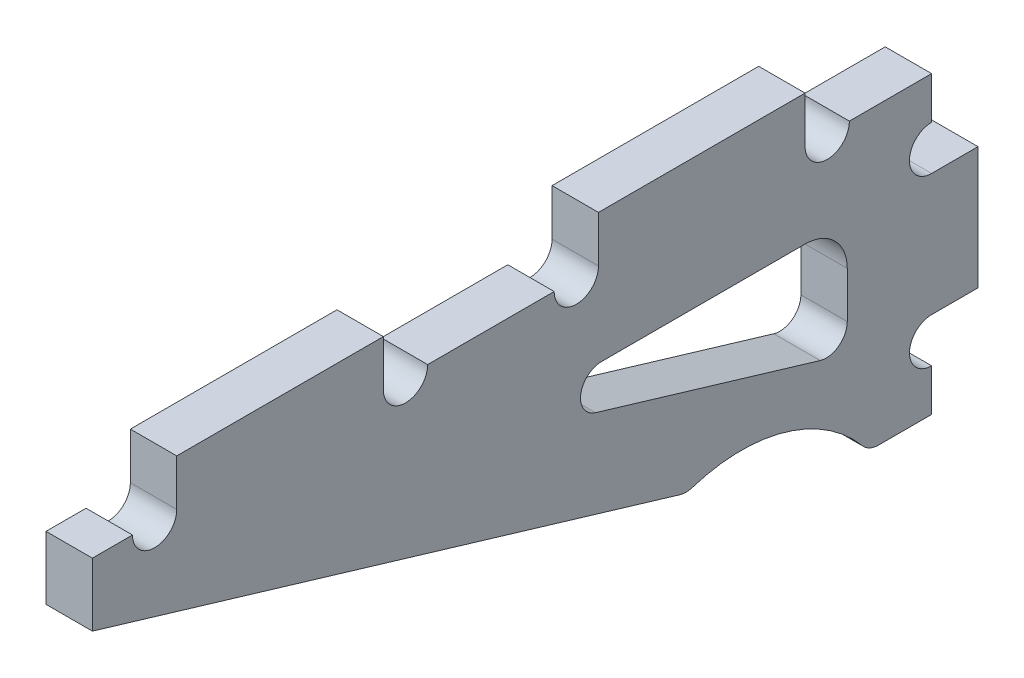
SolidWorks part; units mm, degrees
material "Thornel Mat VMA"
ref_plane "前视基准面" through (0, 0, 0) normal (0, 0, 1) x (1, 0, 0)
ref_plane "上视基准面" through (0, 0, 0) normal (0, 1, 0) x (1, 0, 0)
ref_plane "右视基准面" through (0, 0, 0) normal (1, 0, 0) x (0, 0, -1)
sketch "草图1" plane through (0, 0, 0) normal (1, 0, 0) x (0, 0, -1)
  line L0 (4.9, -1.1) -> (10.9, -1.1)
  line L1 (4.9, -1.1) -> (-4.9, -1.1) construction
  line L2 (4.9, -1.1) -> (4.9, 1.1)
  line L3 (4.9, 1.1) -> (-4.9, 1.1)
  line L4 (-4.9, -1.1) -> (-4.9, 1.1)
  line L5 (4.9, -1.1) -> (-4.9, 1.1) construction
  line L6 (4.9, 1.1) -> (-4.9, -1.1) construction
  line L7 (13.1, -11) -> (10.9, -11)
  line L8 (13.1, -11) -> (13.1, -5.2)
  line L9 (13.1, -5.2) -> (10.9, -5.2)
  line L10 (10.9, -11) -> (10.9, -5.2) construction
  line L11 (13.1, -11) -> (10.9, -5.2) construction
  line L12 (13.1, -5.2) -> (10.9, -11) construction
  line L13 (10.9, -1.1) -> (10.9, -5.2)
  line L14 (-4.9, -1.1) -> (-15.1, -1.1)
  line L17 (7.9, -15.1) -> (10.9, -15.1)
  line L18 (10.9, -15.1) -> (10.9, -11)
  line L19 (-11.5877, -5.1) -> (6.9, -5.1)
  line L20 (6.9, -5.1) -> (6.9, -10.6262)
  line L21 (6.9, -10.6262) -> (-11.5877, -5.1)
  line L22 (-15.1, -1.1) -> (-15.1, 1.1)
  line L23 (-15.1, 1.1) -> (-24.9, 1.1)
  line L24 (-24.9, 1.1) -> (-24.9, -1.1)
  line L25 (-24.9, -1.1) -> (-28.9, -1.1)
  line L26 (-28.9, -1.1) -> (-28.9, -4.1)
  line L27 (-28.9, -4.1) -> (7.9, -15.1)
  line L28 (-20, 1.1) -> (-20, -0.9228) construction
  circle A0 centre (10.9, -4.15) radius 1.05
  circle A1 centre (10.9, -12.05) radius 1.05
  circle A2 centre (5.95, -1.1) radius 1.05
  circle A3 centre (-5.95, -1.1) radius 1.05
  circle A4 centre (-14.05, -1.1) radius 1.05
  circle A5 centre (-25.95, -1.1) radius 1.05
  circle A6 centre (1.8701, -19.5599) radius 7.5
  point P0 (0, 0)
  point P6 (12, -8.1)
  dimension "D7" = 2.1
  dimension "D15" = 15
  dimension "D1" = 14
  dimension "D2" = 5.8
  dimension "D3" = 7
  dimension "D4" = 2.2
  dimension "D5" = 9.8
  dimension "D6" = 10.9
  dimension "D8" = 20
  dimension "D9" = 4
  dimension "D10" = 3
  dimension "D11" = 3
  dimension "D12" = 4
  dimension "D13" = 4
  dimension "D14" = 4
  dimension "D16" = 6
extrude "凸台-拉伸1" add sketch "草图1" along normal blind 2.2
fillet "圆角1" radius 2 1 edges at (1.1, -5.1, -6.9)
fillet "圆角2" radius 1 4 edges at (1.1, -15.1, -7.9) (1.1, -12.5225, 0.723) (1.1, -10.6262, -6.9) (1.1, -5.1, 11.5877)
